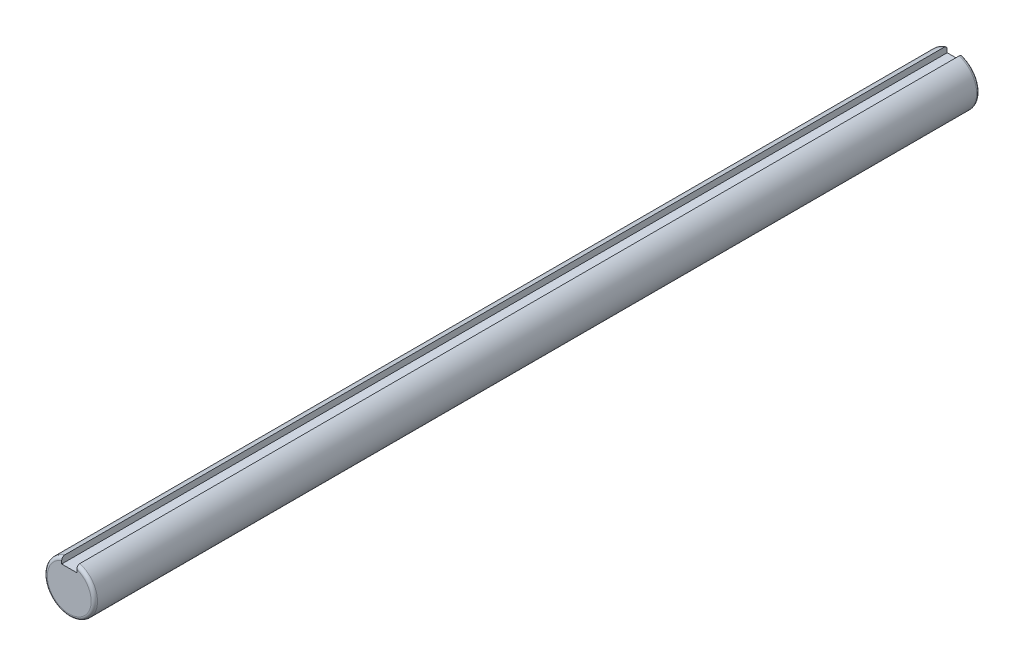
SolidWorks part; units mm, degrees
ref_plane "Front Plane" through (0, 0, 0) normal (0, 0, 1) x (1, 0, 0)
ref_plane "Top Plane" through (0, 0, 0) normal (0, 1, 0) x (1, 0, 0)
ref_plane "Right Plane" through (0, 0, 0) normal (1, 0, 0) x (0, 0, -1)
sketch "Sketch1" plane through (0, 0, 0) normal (0, 0, 1) x (1, 0, 0)
  circle A0 centre (0, 0) radius 3.9688
  dimension "D1" = 7.9375
extrude "Boss-Extrude1" add sketch "Sketch1" along normal blind 140
sketch "Sketch3" plane through (0, 0, 0) normal (0, 0, -1) x (-1, 0, 0)
  line L0 (0, 0) -> (0, 10.894) construction
  line L1 (-1.1906, 3.9688) -> (1.1906, 3.9688)
  line L2 (-1.1906, 3.9688) -> (-1.1906, 2.7781)
  line L3 (-1.1906, 2.7781) -> (1.1906, 2.7781)
  line L4 (1.1906, 3.9688) -> (1.1906, 2.7781)
  circle A2 centre (0, 0) radius 3.9688 construction
  point P7 (0, 3.9688)
  dimension "D1" = 2.3813
  dimension "D2" = 1.1906
extrude "Cut-Extrude2" cut sketch "Sketch3" against normal through all
fillet "Fillet1" radius 0.5 2 edges at (0, -3.9688, 0) (0, -3.9688, 140)
ref_plane "Plane1" through (0, 0, 0) normal (1, 0, 0) x (0, 0, -1)
